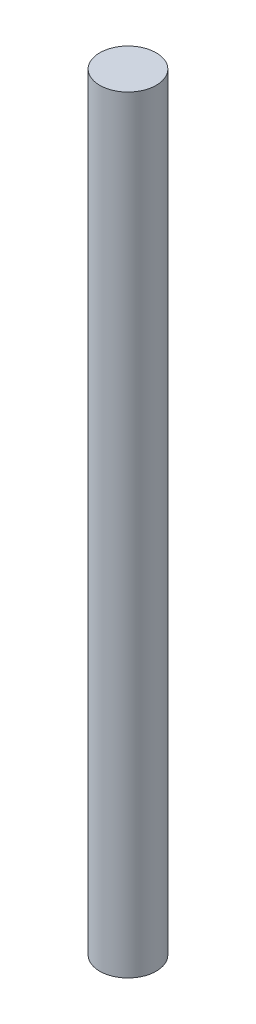
SolidWorks part; units mm, degrees
material "Alloy Steel"
ref_plane "Front Plane" through (0, 0, 0) normal (0, 0, 1) x (1, 0, 0)
ref_plane "Top Plane" through (0, 0, 0) normal (0, 1, 0) x (1, 0, 0)
ref_plane "Right Plane" through (0, 0, 0) normal (1, 0, 0) x (0, 0, -1)
sketch "Sketch1" plane through (0, 0, 0) normal (0, 1, 0) x (1, 0, 0)
  circle A0 centre (0, 0) radius 2.3813
  dimension "D1" = 4.7625
extrude "Boss-Extrude1" add sketch "Sketch1" along normal blind 64.77
